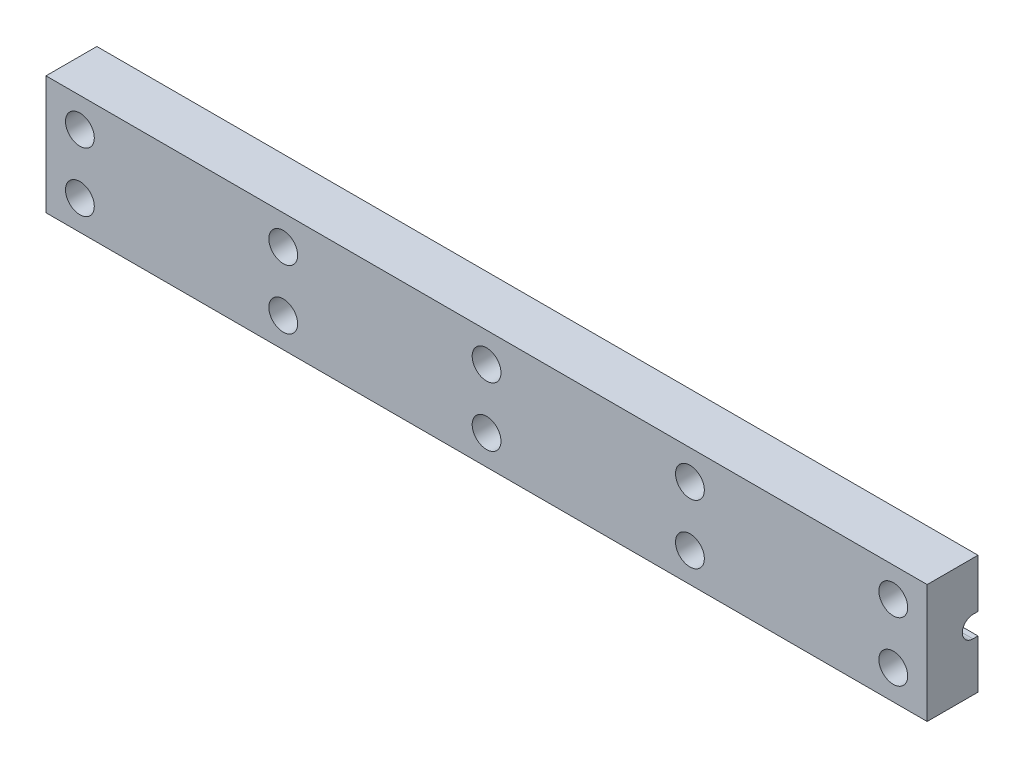
SolidWorks part; units mm, degrees
ref_plane "Front Plane" through (0, 0, 0) normal (0, 0, 1) x (1, 0, 0)
ref_plane "Top Plane" through (0, 0, 0) normal (0, 1, 0) x (1, 0, 0)
ref_plane "Right Plane" through (0, 0, 0) normal (1, 0, 0) x (0, 0, -1)
ref_plane "Plane1" through (190.6451, 0, 0) normal (1, 0, 0) x (0, 0, -1)
sketch "Sketch1" plane through (190.6451, 0, 0) normal (1, 0, 0) x (0, 0, -1)
  line L0 (-246.9709, 208.1635) -> (-246.9709, 205.1635) construction
  line L1 (-240.9709, 205.1635) -> (-240.9709, 208.1635) construction
  line L2 (-240.9709, 208.1635) -> (-246.9709, 208.1635) construction
  line L3 (-240.9709, 199.9135) -> (-241.5709, 199.9135) construction
  line L4 (-241.5709, 202.4135) -> (-240.9709, 202.4135) construction
  line L5 (-240.9709, 202.4135) -> (-240.9709, 205.1635) construction
  line L6 (-246.9709, 205.1635) -> (-246.9709, 197.1635) construction
  line L7 (-240.9709, 197.1635) -> (-240.9709, 199.9135) construction
  line L8 (-246.9709, 197.1635) -> (-246.9709, 194.1635) construction
  line L9 (-246.9709, 194.1635) -> (-240.9709, 194.1635) construction
  line L10 (-240.9709, 194.1635) -> (-240.9709, 197.1635) construction
  line L11 (-246.9709, 208.1635) -> (-246.9709, 205.1635)
  line L12 (-240.9709, 205.1635) -> (-240.9709, 208.1635)
  line L13 (-240.9709, 208.1635) -> (-246.9709, 208.1635)
  line L14 (-240.9709, 199.9135) -> (-241.5709, 199.9135)
  line L15 (-241.5709, 202.4135) -> (-240.9709, 202.4135)
  line L16 (-240.9709, 202.4135) -> (-240.9709, 205.1635)
  line L17 (-246.9709, 205.1635) -> (-246.9709, 197.1635)
  line L18 (-240.9709, 197.1635) -> (-240.9709, 199.9135)
  line L19 (-246.9709, 197.1635) -> (-246.9709, 194.1635)
  line L20 (-246.9709, 194.1635) -> (-240.9709, 194.1635)
  line L21 (-240.9709, 194.1635) -> (-240.9709, 197.1635)
  arc A0 (-241.5709, 202.4135) -> (-241.5709, 199.9135) centre (-241.5709, 201.1635) ccw construction
  arc A1 (-241.5709, 202.4135) -> (-241.5709, 199.9135) centre (-241.5709, 201.1635) ccw
extrude "Boss-Extrude1" add sketch "Sketch1" along normal blind 60 and the other way blind 20
sketch "Sketch2" plane through (0, 0, 246.9709) normal (0, 0, 1) x (1, 0, 0)
  line L0 (170.6451, 201.1635) -> (250.6451, 201.1635) construction
  line L1 (170.6451, 208.1635) -> (170.6451, 194.1635) construction
  line L2 (170.6451, 201.1635) -> (170.6451, 208.1635) construction
  line L3 (170.6451, 204.6635) -> (250.6451, 204.6635) construction
  line L4 (170.6451, 194.1635) -> (250.6451, 194.1635)
  line L5 (250.6451, 194.1635) -> (250.6451, 208.1635)
  line L6 (250.6451, 208.1635) -> (170.6451, 208.1635)
  line L7 (170.6451, 208.1635) -> (170.6451, 194.1635)
  line L8 (170.6451, 194.1635) -> (250.6451, 194.1635) construction
  line L9 (250.6451, 194.1635) -> (250.6451, 208.1635) construction
  line L10 (250.6451, 208.1635) -> (170.6451, 208.1635) construction
  line L12 (250.6451, 201.1635) -> (250.6451, 194.1635)
  line L13 (250.6451, 197.6635) -> (170.6451, 197.6635) construction
  line L15 (246.6451, 197.6635) -> (250.6451, 197.6635)
  line L16 (174.6451, 197.6635) -> (170.6451, 197.6635)
  line L17 (246.6451, 197.6635) -> (222.6451, 197.6635) construction
  line L18 (174.6451, 197.6635) -> (198.6451, 197.6635)
  line L20 (246.6451, 204.6635) -> (222.6451, 204.6635) construction
  circle A0 centre (246.6451, 197.6635) radius 1.7
  circle A2 centre (174.6451, 197.6635) radius 1.7
  circle A3 centre (198.6451, 197.6635) radius 1.7
  circle A4 centre (222.6451, 197.6635) radius 1.7
  circle A5 centre (174.6451, 204.6635) radius 1.7
  circle A6 centre (198.6451, 204.6635) radius 1.7
  circle A7 centre (222.6451, 204.6635) radius 1.7
  circle A8 centre (246.6451, 204.6635) radius 1.7
  dimension "D2" = 3.4
  dimension "D3" = 4
  dimension "D4" = 4
  dimension "D5" = 24
  dimension "D6" = 24
  dimension "D1" = 0
extrude "Cut-Extrude1" cut sketch "Sketch2" against normal blind 10
sketch "Sketch3" plane through (170.6451, 0, 0) normal (-1, 0, 0) x (0, 0, 1)
  line L7 (246.9709, 208.1635) -> (240.9709, 208.1635)
  line L8 (240.9709, 208.1635) -> (240.9709, 202.4135)
  line L9 (240.9709, 202.4135) -> (241.5709, 202.4135)
  line L10 (241.5709, 199.9135) -> (240.9709, 199.9135)
  line L11 (240.9709, 199.9135) -> (240.9709, 194.1635)
  line L12 (240.9709, 194.1635) -> (246.9709, 194.1635)
  line L13 (246.9709, 194.1635) -> (246.9709, 208.1635)
  line L14 (246.9709, 208.1635) -> (240.9709, 208.1635)
  line L15 (240.9709, 208.1635) -> (240.9709, 202.4135)
  line L16 (240.9709, 202.4135) -> (241.5709, 202.4135)
  line L17 (241.5709, 199.9135) -> (240.9709, 199.9135)
  line L18 (240.9709, 199.9135) -> (240.9709, 194.1635)
  line L19 (240.9709, 194.1635) -> (246.9709, 194.1635)
  line L20 (246.9709, 194.1635) -> (246.9709, 208.1635)
  arc A1 (241.5709, 199.9135) -> (241.5709, 202.4135) centre (241.5709, 201.1635) ccw
  arc A2 (241.5709, 199.9135) -> (241.5709, 202.4135) centre (241.5709, 201.1635) ccw
  dimension "D1" = 0
extrude "Boss-Extrude2" add sketch "Sketch3" along normal blind 24
sketch "Sketch4" plane through (0, 0, 246.9709) normal (0, 0, 1) x (1, 0, 0)
  line L0 (174.6451, 197.6635) -> (150.6451, 197.6635) construction
  line L1 (174.6451, 204.6635) -> (150.6451, 204.6635) construction
  circle A0 centre (174.6451, 204.6635) radius 1.7 construction
  circle A1 centre (174.6451, 197.6635) radius 1.7 construction
  circle A2 centre (174.6451, 204.6635) radius 1.7
  circle A3 centre (174.6451, 197.6635) radius 1.7
  circle A4 centre (150.6451, 197.6635) radius 1.7
  circle A5 centre (150.6451, 204.6635) radius 1.7
  dimension "D1" = 24
extrude "Cut-Extrude2" cut sketch "Sketch4" against normal blind 24
equation "\"D6@Sketch2\"=\"D5@Sketch2\""
